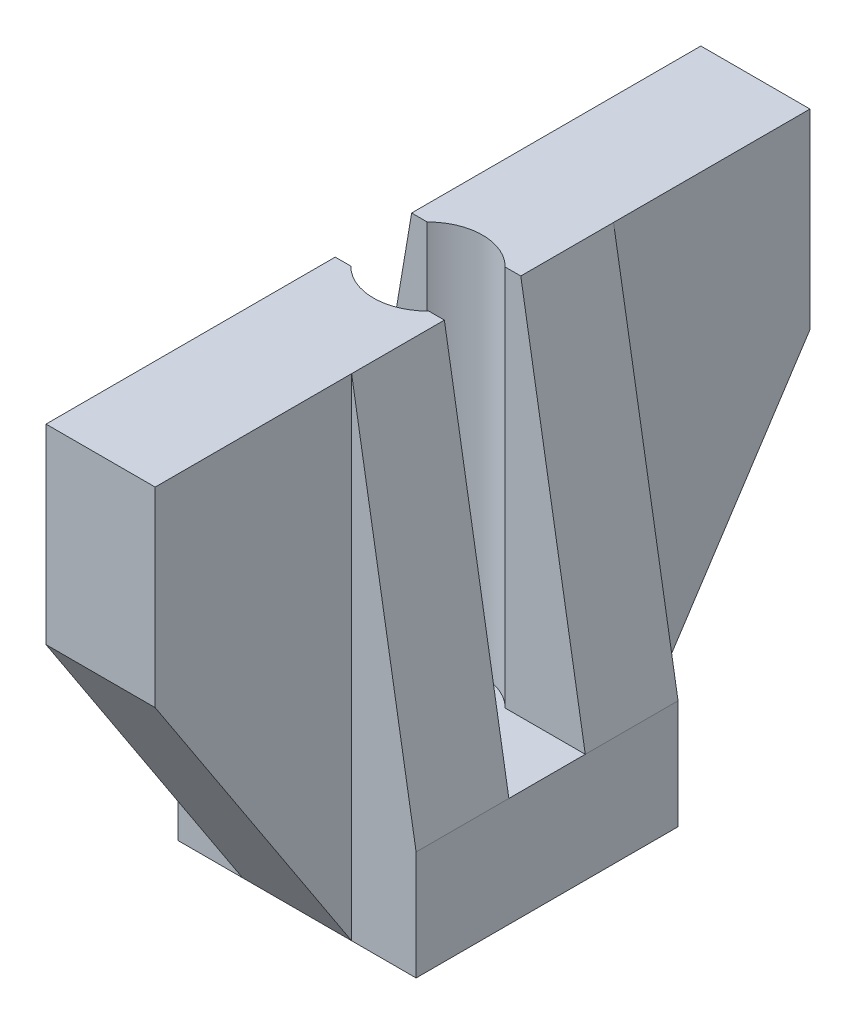
SolidWorks part; units mm, degrees
ref_plane "Front Plane" through (0, 0, 0) normal (0, 0, 1) x (1, 0, 0)
ref_plane "Top Plane" through (0, 0, 0) normal (0, 1, 0) x (1, 0, 0)
ref_plane "Right Plane" through (0, 0, 0) normal (1, 0, 0) x (0, 0, -1)
sketch "Sketch1" plane through (0, 0, 0) normal (0, 1, 0) x (1, 0, 0)
  line L1 (10.91, -12) -> (-10.91, -12)
  line L2 (10.91, -12) -> (10.91, 12)
  line L3 (10.91, 12) -> (-10.91, 12)
  line L4 (-10.91, -12) -> (-10.91, 12)
  line L5 (3.9761, -4.3734) -> (2.7917, -3.0706) construction
  circle A1 centre (0, 0) radius 4.15
  dimension "D2" = 8.3
  dimension "D3" = 24
  dimension "D4" = 21.82
extrude "Boss-Extrude1" add sketch "Sketch1" along normal mid plane 10
sketch "Sketch2" plane through (0, -5, 0) normal (0, -1, 0) x (1, 0, 0)
  line L0 (-7.7942, 0) -> (7.7942, 0) construction
  line L7 (-7.7942, 0) -> (-3.8971, -6.75)
  line L8 (-3.8971, -6.75) -> (3.8971, -6.75)
  line L9 (3.8971, -6.75) -> (7.7942, 0)
  line L10 (7.7942, 0) -> (3.8971, 6.75)
  line L11 (3.8971, 6.75) -> (-3.8971, 6.75)
  line L12 (-3.8971, 6.75) -> (-7.7942, 0)
  circle A0 centre (0, 0) radius 6.75 construction
  dimension "D1" = 13.5
extrude "Cut-Extrude1" cut sketch "Sketch2" against normal blind 6.5
sketch "Sketch3" plane through (0, 5, 0) normal (0, 1, 0) x (1, 0, 0)
  line L0 (-3.5707, 3.5) -> (-5, 3.5)
  line L1 (-5, 30) -> (5, 30)
  line L2 (-5, 30) -> (-5, 3.5)
  line L3 (-5, -30) -> (5, -30)
  line L4 (5, 30) -> (5, 3.5)
  line L5 (-5, 30) -> (5, -30) construction
  line L6 (-5, -30) -> (5, 30) construction
  line L7 (-5, 0) -> (5, 0) construction
  line L8 (0, 0) -> (0, 3.6465) construction
  line L9 (3.5707, 3.5) -> (5, 3.5)
  line L10 (3.5707, -3.5) -> (5, -3.5)
  line L11 (-3.5707, -3.5) -> (-5, -3.5)
  line L12 (-5, -3.5) -> (-5, -30)
  line L13 (5, -3.5) -> (5, -30)
  arc A0 (-3.5707, -3.5) -> (3.5707, -3.5) centre (0, 0) ccw
  arc A1 (3.5707, 3.5) -> (-3.5707, 3.5) centre (0, 0) ccw
  point P0 (0, 0)
  dimension "D1" = 10
  dimension "D2" = 60
  dimension "D3" = 3.5
extrude "Boss-Extrude2" add sketch "Sketch3" along normal blind 35
sketch "Sketch4" plane through (5, 0, 0) normal (1, 0, 0) x (0, 0, -1)
  line L4 (0, 1.9098) -> (0, -1.8216) construction
  line L9 (-10.1664, -5) -> (-10.1598, 5.0005)
  line L14 (10.1664, -5) -> (10.1598, 5.0005)
  line L15 (-12, -5) -> (-10.1664, -5)
  line L17 (12, -5) -> (10.1664, -5)
  line L18 (-12, -5) -> (-30, 22.5)
  line L19 (30, 22.5) -> (12, -5)
  line L20 (-30, 40) -> (-30, 5) construction
  line L21 (-10.1598, 5.0005) -> (-30, 22.5)
  line L22 (10.1598, 5.0005) -> (30, 22.5)
extrude "Boss-Extrude3" add sketch "Sketch4" against normal blind 10
sketch "Sketch5" plane through (5, 0, 0) normal (1, 0, 0) x (0, 0, -1)
  line L0 (-18.5455, 5) -> (-30, 22.5)
  line L1 (-30, 40) -> (-30, 5) construction
  line L2 (-30, 22.5) -> (-30, 5)
  line L3 (-30, 5) -> (-18.5455, 5)
  line L4 (0, 0) -> (0, 13.75) construction
  line L5 (30, 22.5) -> (30, 5)
  line L6 (18.5455, 5) -> (30, 22.5)
  line L7 (30, 5) -> (18.5455, 5)
extrude "Cut-Extrude2" cut sketch "Sketch5" against normal blind 10
sketch "Sketch6" plane through (0, 0, -30) normal (0, 0, -1) x (-1, 0, 0)
  line L0 (-10.91, 5) -> (-5, 40)
  line L1 (-5, 40) -> (-5, 5)
  line L2 (-5, 5) -> (-10.91, 5)
  line L3 (0, 0) -> (0, 22.5) construction
  line L4 (5, 22.5) -> (-5, 22.5) construction
  line L5 (5, 40) -> (5, 5)
  line L6 (10.91, 5) -> (5, 40)
  line L7 (5, 5) -> (10.91, 5)
  line L8 (-10.91, 5) -> (-5, 5) construction
extrude "Boss-Extrude4" add sketch "Sketch6" against normal blind 8.5 from offset 18 contours L2 L0 L1 | L5 L7 L6 offset against normal yes
mirror "Mirror9" about plane through (0, 0, 0) normal (0, 0, 1) of "Boss-Extrude4"
